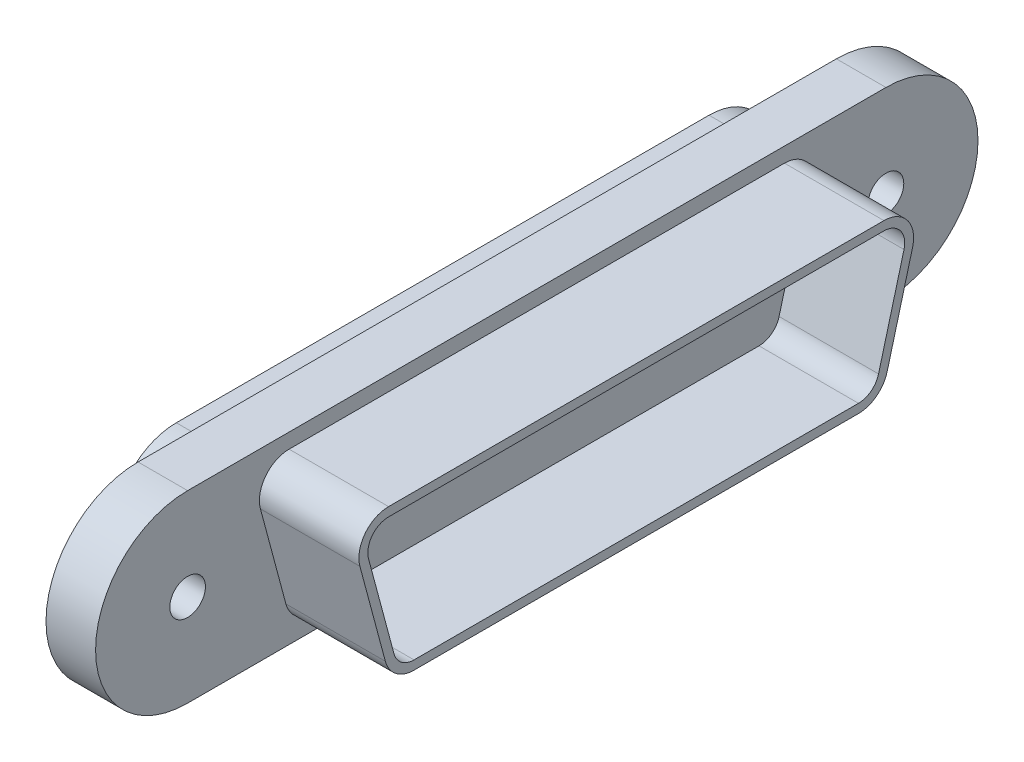
SolidWorks part; units mm, degrees
ref_plane "Front Plane" through (0, 0, 0) normal (0, 0, 1) x (1, 0, 0)
ref_plane "Top Plane" through (0, 0, 0) normal (0, 1, 0) x (1, 0, 0)
ref_plane "Right Plane" through (0, 0, 0) normal (1, 0, 0) x (0, 0, -1)
sketch "Sketch1" plane through (0, 0, 0) normal (1, 0, 0) x (0, 0, -1)
  line L0 (-29.8704, 0) -> (29.8704, 0) construction
  line L1 (-29.8704, 7.874) -> (29.8704, 7.874)
  line L2 (-29.8704, -7.874) -> (29.8704, -7.874)
  arc A0 (-29.8704, 7.874) -> (-29.8704, -7.874) centre (-29.8704, 0) ccw
  arc A1 (29.8704, -7.874) -> (29.8704, 7.874) centre (29.8704, 0) ccw
  point P2 (0, 0)
  dimension "D1" = 59.7408
  dimension "D2" = 15.748
extrude "Boss-Extrude1" add sketch "Sketch1" along normal blind 4.2418
sketch "Sketch2" plane through (4.2418, 0, 0) normal (1, 0, 0) x (0, 0, -1)
  line L0 (-21.1881, 6.604) -> (21.1881, 6.604)
  line L1 (-19.0102, -6.604) -> (19.0102, -6.604)
  line L2 (21.4637, -4.7214) -> (23.6416, 3.4066)
  line L3 (-21.4637, -4.7214) -> (-23.6416, 3.4066)
  line L4 (29.8704, 7.874) -> (-29.8704, 7.874) construction
  line L5 (-29.8704, -7.874) -> (29.8704, -7.874) construction
  line L6 (0, 0) -> (0, 7.874) construction
  line L7 (-24.4983, 6.604) -> (-24.4983, -7.874) construction
  line L8 (24.4983, 6.604) -> (24.4983, -7.874) construction
  arc A0 (-23.6416, 3.4066) -> (-21.1881, 6.604) centre (-21.1881, 4.064) cw
  arc A1 (21.1881, 6.604) -> (23.6416, 3.4066) centre (21.1881, 4.064) cw
  arc A2 (21.4637, -4.7214) -> (19.0102, -6.604) centre (19.0102, -4.064) cw
  arc A3 (-21.4637, -4.7214) -> (-19.0102, -6.604) centre (-19.0102, -4.064) ccw
  dimension "D6" = 2.54
  dimension "D1" = 1.27
  dimension "D2" = 1.27
  dimension "D3" = 48.9966
  dimension "D4" = 15
  dimension "D5" = 15
extrude "Boss-Extrude2" add sketch "Sketch2" along normal blind 8.509
sketch "Sketch3" plane through (12.7508, 0, 0) normal (1, 0, 0) x (0, 0, -1)
  line L8 (-22.9055, 3.6038) -> (-20.7276, -4.5242)
  line L9 (-19.0102, -5.842) -> (19.0102, -5.842)
  line L10 (20.7276, -4.5242) -> (22.9055, 3.6038)
  line L11 (21.1881, 5.842) -> (-21.1881, 5.842)
  line L12 (-22.9055, 3.6038) -> (-20.7276, -4.5242)
  line L13 (-19.0102, -5.842) -> (19.0102, -5.842)
  line L14 (20.7276, -4.5242) -> (22.9055, 3.6038)
  line L15 (21.1881, 5.842) -> (-21.1881, 5.842)
  arc A8 (-21.1881, 5.842) -> (-22.9055, 3.6038) centre (-21.1881, 4.064) ccw
  arc A9 (-20.7276, -4.5242) -> (-19.0102, -5.842) centre (-19.0102, -4.064) ccw
  arc A10 (19.0102, -5.842) -> (20.7276, -4.5242) centre (19.0102, -4.064) ccw
  arc A11 (22.9055, 3.6038) -> (21.1881, 5.842) centre (21.1881, 4.064) ccw
  arc A12 (-21.1881, 5.842) -> (-22.9055, 3.6038) centre (-21.1881, 4.064) ccw
  arc A13 (-20.7276, -4.5242) -> (-19.0102, -5.842) centre (-19.0102, -4.064) ccw
  arc A14 (19.0102, -5.842) -> (20.7276, -4.5242) centre (19.0102, -4.064) ccw
  arc A15 (22.9055, 3.6038) -> (21.1881, 5.842) centre (21.1881, 4.064) ccw
  dimension "D1" = 0.762
extrude "Cut-Extrude1" cut sketch "Sketch3" against normal blind 8.509
hole_wizard "X (0.397) Diameter Hole1" positions "Sketch5" profile "Sketch6" hole size "X" standard "ANSI Inch" end condition through all
sketch "Sketch5" plane through (4.2418, 0, 0) normal (1, 0, 0) x (0, 0, -1)
  arc A0 (-29.8704, 7.874) -> (-29.8704, -7.874) centre (-29.8704, 0) ccw construction
  arc A1 (29.8704, -7.874) -> (29.8704, 7.874) centre (29.8704, 0) ccw construction
  point P0 (-29.8704, 0)
  point P2 (29.8704, 0)
sketch "Sketch6" plane through (4.2418, 0, 29.8704) normal (0, 1, 0) x (0, 0, -1)
  line L0 (0, 0) -> (0, 4.2418)
  line L1 (0, 4.2418) -> (1.524, 4.2418)
  line L2 (1.524, 4.2418) -> (1.524, 0)
  line L5 (1.524, 0) -> (0, 0)
  line L11 (0, -6.35) -> (0, 107.95) construction
  dimension "Thru Hole Dia." = 3.048
  dimension "Thru Hole Depth" = 4.2418
sketch "Sketch7" plane through (0, 0, 0) normal (-1, 0, 0) x (0, 0, 1)
  line L0 (-22.7863, 0) -> (22.7863, 0) construction
  line L1 (-22.7863, 5.334) -> (22.7863, 5.334)
  line L2 (-22.7863, -5.334) -> (22.7863, -5.334)
  line L3 (-29.8704, 7.874) -> (29.8704, 7.874) construction
  arc A0 (-22.7863, 5.334) -> (-22.7863, -5.334) centre (-22.7863, 0) ccw
  arc A1 (22.7863, -5.334) -> (22.7863, 5.334) centre (22.7863, 0) ccw
  point P2 (0, 0)
  dimension "D1" = 2.54
extrude "Boss-Extrude3" add sketch "Sketch7" along normal blind 3.81
